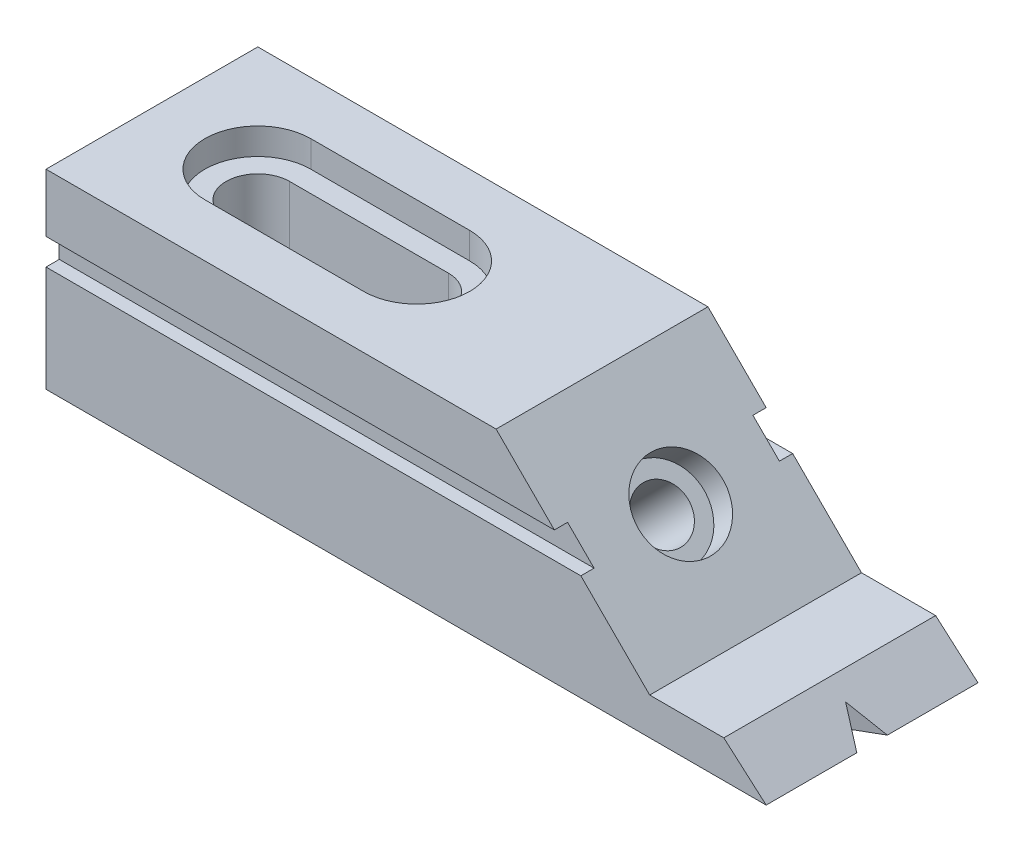
SolidWorks part; units mm, degrees
ref_plane "Front Plane" through (0, 0, 0) normal (0, 0, 1) x (1, 0, 0)
ref_plane "Top Plane" through (0, 0, 0) normal (0, 1, 0) x (1, 0, 0)
ref_plane "Right Plane" through (0, 0, 0) normal (1, 0, 0) x (0, 0, -1)
sketch "Sketch1" plane through (0, 0, 0) normal (0, 0, 1) x (1, 0, 0)
  line L0 (0, 0) -> (172.72, 0)
  line L1 (55, 0) -> (-55, 0) construction
  line L2 (172.72, 0) -> (162.56, 8.89)
  line L3 (162.56, 8.89) -> (144.78, 8.89)
  line L4 (144.78, 8.89) -> (107.95, 45.72)
  line L5 (107.95, 45.72) -> (0, 45.72)
  line L6 (0, -55) -> (0, 55) construction
  line L7 (0, 45.72) -> (0, 0)
  dimension "D1" = 172.72
  dimension "D2" = 107.95
  dimension "D3" = 17.78
  dimension "D4" = 45
  dimension "D5" = 45.72
  dimension "D6" = 8.89
extrude "Boss-Extrude1" add sketch "Sketch1" along normal mid plane 50.8
sketch "Sketch2" plane through (76.835, 76.835, 0) normal (0.7071, 0.7071, 0) x (0, 0, -1)
  line L0 (0, 25.146) -> (0, -25.146) construction
  line L1 (-25.4, -96.0887) -> (25.4, -96.0887) construction
  circle A0 centre (0, -70.6887) radius 6.35
  dimension "D1" = 12.7
  dimension "D2" = 25.4
extrude "Cut-Extrude1" cut sketch "Sketch2" against normal through all
sketch "Sketch3" plane through (76.835, 76.835, 0) normal (0.7071, 0.7071, 0) x (0, 0, -1)
  circle A0 centre (0, -70.6887) radius 10.16
  dimension "D1" = 20.32
extrude "Cut-Extrude2" cut sketch "Sketch3" against normal blind 6.35
sketch "Sketch5" plane through (0, 8.89, 0) normal (0, 1, 0) x (1, 0, 0)
  line L0 (148.8515, 0) -> (177.6024, 0) construction
  line L1 (-25.146, 0) -> (25.146, 0) construction
  line L2 (166.37, 0) -> (177.6024, 6.485)
  line L3 (177.6024, 6.485) -> (177.6024, -6.485)
  line L4 (177.6024, -6.485) -> (166.37, 0)
  line L5 (172.72, -25.4) -> (172.72, 25.4) construction
  point P7 (0, 0)
  dimension "D1" = 60
  dimension "D2" = 6.35
extrude "Cut-Extrude3" cut sketch "Sketch5" against normal through all
sketch "Sketch6" plane through (0, 0, 0) normal (1, 0, 0) x (0, 0, -1)
  line L0 (0, 46.7579) -> (0, -4.1345) construction
  line L1 (0, 25.146) -> (0, -25.146) construction
  line L2 (-25.4, 31.75) -> (-22.225, 31.75)
  line L3 (-25.4, 8.89) -> (-25.4, 45.72) construction
  line L4 (25.4, 31.75) -> (22.225, 31.75)
  line L5 (-22.225, 31.75) -> (-22.225, 25.4)
  line L6 (22.225, 31.75) -> (22.225, 25.4)
  line L7 (-22.225, 25.4) -> (-25.4, 25.4)
  line L8 (22.225, 25.4) -> (25.4, 25.4)
  line L9 (-25.4, 25.4) -> (-25.4, 31.75)
  line L10 (25.4, 25.4) -> (25.4, 31.75)
  line L11 (27.94, 0) -> (-27.94, 0) construction
  dimension "D1" = 25.4
  dimension "D2" = 6.35
  dimension "D3" = 3.175
extrude "Cut-Extrude4" cut sketch "Sketch6" along normal through all
sketch "Sketch7" plane through (0, 45.72, 0) normal (0, 1, 0) x (1, 0, 0)
  line L0 (25.4, 0) -> (63.5, 0) construction
  line L1 (-25.146, 0) -> (25.146, 0) construction
  line L2 (25.4, 12.7) -> (63.5, 12.7)
  line L3 (25.4, -12.7) -> (63.5, -12.7)
  line L4 (0, -25.146) -> (0, 25.146) construction
  arc A0 (25.4, 12.7) -> (25.4, -12.7) centre (25.4, 0) ccw
  arc A1 (63.5, -12.7) -> (63.5, 12.7) centre (63.5, 0) ccw
  point P5 (44.45, 0)
  point P12 (7.3614, 1.5721)
  dimension "D1" = 38.1
  dimension "D2" = 25.4
  dimension "D3" = 25.4
extrude "Cut-Extrude5" cut sketch "Sketch7" against normal blind 6.35
sketch "Sketch8" plane through (0, 39.37, 0) normal (0, 1, 0) x (1, 0, 0)
  line L4 (25.4, -7.62) -> (63.5, -7.62)
  line L5 (63.5, 7.62) -> (25.4, 7.62)
  line L6 (25.4, -7.62) -> (63.5, -7.62)
  line L7 (63.5, 7.62) -> (25.4, 7.62)
  arc A4 (25.4, 7.62) -> (25.4, -7.62) centre (25.4, 0) ccw
  arc A5 (63.5, -7.62) -> (63.5, 7.62) centre (63.5, 0) ccw
  arc A6 (25.4, 7.62) -> (25.4, -7.62) centre (25.4, 0) ccw
  arc A7 (63.5, -7.62) -> (63.5, 7.62) centre (63.5, 0) ccw
  dimension "D1" = 5.08
extrude "Cut-Extrude6" cut sketch "Sketch8" against normal through all
